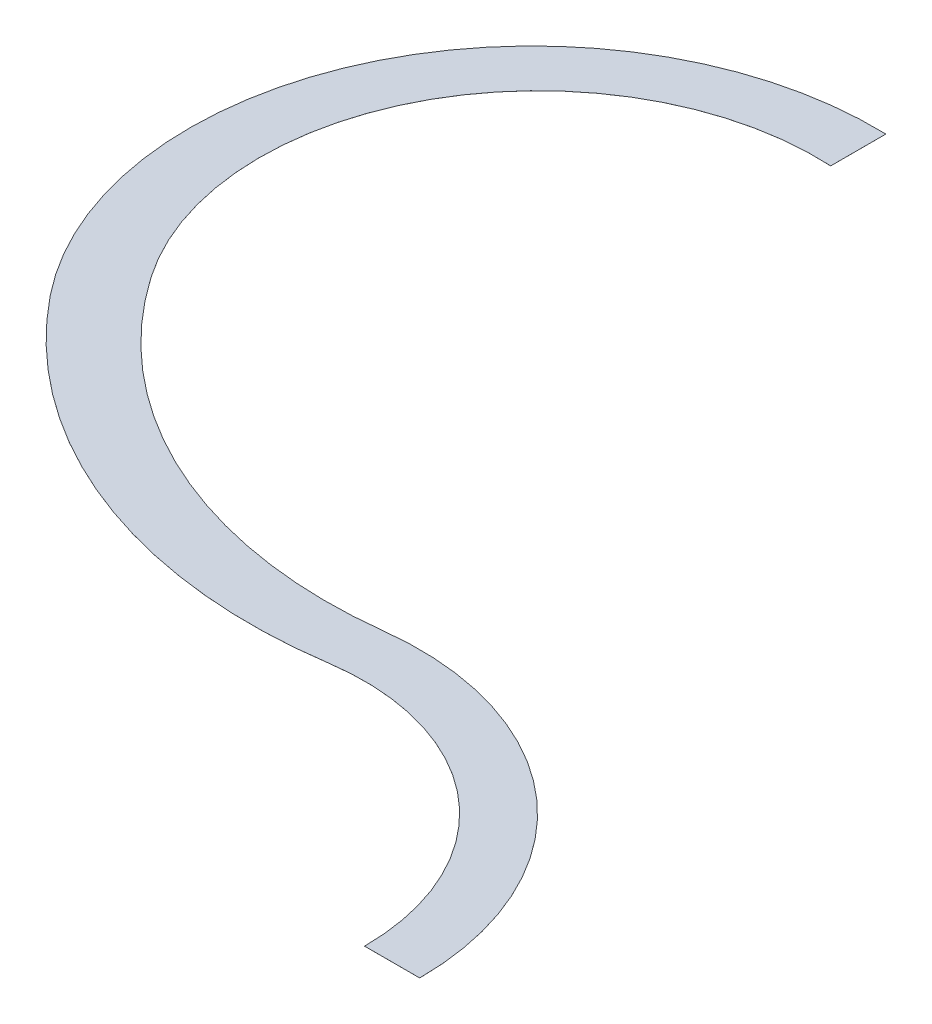
SolidWorks part; units mm, degrees
ref_plane "Plano frontal" through (0, 0, 0) normal (0, 0, 1) x (1, 0, 0)
ref_plane "Plano superior" through (0, 0, 0) normal (0, 1, 0) x (1, 0, 0)
ref_plane "Plano direito" through (0, 0, 0) normal (1, 0, 0) x (0, 0, -1)
sketch "Esboço1" plane through (0, 0, 0) normal (0, 1, 0) x (1, 0, 0)
  line L0 (-1093, 595.536) -> (-1073, 595.536)
  line L1 (0, 0) -> (18.9344, 0)
  line L2 (0, 0) -> (0, 766.8662)
  line L3 (0, 766.8662) -> (18.9344, 766.8662)
  line L4 (18.9344, 0) -> (18.9344, 766.8662)
  line L5 (-381.6968, 766.8662) -> (-362.7624, 766.8662)
  line L6 (-381.6968, 766.8662) -> (-381.6968, 345.536)
  line L7 (-381.6968, 345.536) -> (-362.7624, 345.536)
  line L8 (-362.7624, 766.8662) -> (-362.7624, 345.536)
  line L9 (-858.9344, 645.536) -> (-840, 645.536)
  line L10 (-858.9344, 645.536) -> (-858.9344, 345.536)
  line L11 (-858.9344, 345.536) -> (-840, 345.536)
  line L12 (-840, 645.536) -> (-840, 345.536)
  line L13 (-853.5858, 925.2213) -> (-1253.5858, 925.2213)
  line L14 (-853.5858, 925.2213) -> (-853.5858, 945.2213)
  line L15 (-853.5858, 945.2213) -> (-1253.5858, 945.2213)
  line L16 (-1253.5858, 925.2213) -> (-1253.5858, 945.2213)
  line L17 (-1093, 595.536) -> (-1093, 195.536)
  line L18 (-1093, 195.536) -> (-1073, 195.536)
  line L19 (-1073, 595.536) -> (-1073, 195.536)
  line L21 (-858.9344, 427.7897) -> (-1250.0103, 427.7897)
  line L23 (-858.9344, 407.7897) -> (-1250.0103, 407.7897)
  line L24 (-1250.0103, 427.7897) -> (-1250.0103, 407.7897)
  line L33 (-1439.6613, 239.7512) -> (-1560.0448, 239.7512)
  line L34 (-1439.6613, 239.7512) -> (-1439.6613, 219.7512)
  line L35 (-1439.6613, 219.7512) -> (-1560.0448, 219.7512)
  line L36 (-1560.0448, 239.7512) -> (-1560.0448, 219.7512)
  line L37 (-1627.2015, 576.144) -> (-1607.2015, 576.144)
  line L38 (-1627.2015, 576.144) -> (-1627.2015, 317.0654)
  line L39 (-1627.2015, 317.0654) -> (-1607.2015, 317.0654)
  line L40 (-1607.2015, 576.144) -> (-1607.2015, 317.0654)
  line L41 (-1627.2015, 769.6927) -> (-1607.2015, 769.6927)
  line L42 (-1627.2015, 769.6927) -> (-1627.2015, 1019.6927)
  line L43 (-1627.2015, 1019.6927) -> (-1607.2015, 1019.6927)
  line L44 (-1607.2015, 769.6927) -> (-1607.2015, 1019.6927)
  line L45 (471.067, 763.0326) -> (491.067, 763.0326)
  line L46 (310.4812, 1092.7179) -> (310.4812, 1112.7179)
  arc A6 (-381.6968, 766.8662) -> (18.9344, 766.8662) centre (-181.3812, 766.8662) cw
  arc A7 (-362.7624, 766.8662) -> (0, 766.8662) centre (-181.3812, 766.8662) cw
  arc A8 (-362.7624, 345.536) -> (-858.9344, 345.536) centre (-610.8484, 345.536) cw
  arc A9 (-381.6968, 345.536) -> (-840, 345.536) centre (-610.8484, 345.536) cw
  arc A10 (-840, 645.536) -> (-803.6955, 702.0415) centre (-777.8744, 645.536) cw
  arc A11 (-803.6955, 702.0415) -> (-853.5858, 945.2213) centre (-856.6336, 817.8884) ccw
  arc A12 (-858.9344, 645.536) -> (-814.4955, 717.9247) centre (-777.7563, 645.536) cw
  arc A13 (-814.4955, 717.9247) -> (-853.5858, 925.2213) centre (-864.2122, 815.8835) ccw
  arc A14 (-1093, 595.536) -> (-1188.5366, 677.9223) centre (-1176.2913, 595.536) ccw
  arc A15 (-1188.5366, 677.9223) -> (-1354.3411, 742.8189) centre (-1214.8489, 854.9525) cw
  arc A16 (-1354.3411, 742.8189) -> (-1253.5858, 945.2213) centre (-1257.3278, 820.805) cw
  arc A17 (-1073, 595.536) -> (-1188.5366, 698.0004) centre (-1176.2038, 595.536) ccw
  arc A18 (-1188.5366, 698.0004) -> (-1341.8208, 766.8662) centre (-1207.9995, 859.705) cw
  arc A19 (-1341.8208, 766.8662) -> (-1253.5858, 925.2213) centre (-1258.876, 824.4093) cw
  arc A22 (-1368.7558, 309.7722) -> (-1439.6613, 219.7512) centre (-1474.849, 320.402) cw
  arc A23 (-1388.5562, 309.7722) -> (-1439.6613, 239.7512) centre (-1477.6183, 321.1143) cw
  arc A24 (-1388.5562, 309.7722) -> (-1250.0103, 427.7897) centre (-1254.4723, 292.6965) cw
  arc A25 (-1607.2015, 317.0654) -> (-1560.0448, 239.7512) centre (-1520.2441, 317.0654) ccw
  arc A26 (-1627.2015, 317.0654) -> (-1560.0448, 219.7512) centre (-1523.1159, 317.0654) ccw
  arc A27 (-1368.7558, 309.7722) -> (-1250.0103, 407.7897) centre (-1259.9289, 298.8686) cw
  arc A28 (471.067, 763.0326) -> (375.5304, 845.4189) centre (387.7756, 763.0326) ccw
  arc A29 (375.5304, 845.4189) -> (209.7258, 910.3155) centre (349.218, 1022.4491) cw
  arc A30 (209.7258, 910.3155) -> (310.4812, 1112.7179) centre (306.7392, 988.3016) cw
  arc A31 (491.067, 763.0326) -> (375.5304, 865.497) centre (387.8631, 763.0326) ccw
  arc A32 (375.5304, 865.497) -> (222.2461, 934.3628) centre (356.0674, 1027.2016) cw
  arc A33 (222.2461, 934.3628) -> (310.4812, 1092.7179) centre (305.1909, 991.9059) cw
extrude "Ressalto-extrusão12" add sketch "Esboço1" along normal blind 0.01 contours A29 A30 L46 A33 A32 A31 L45 A28
